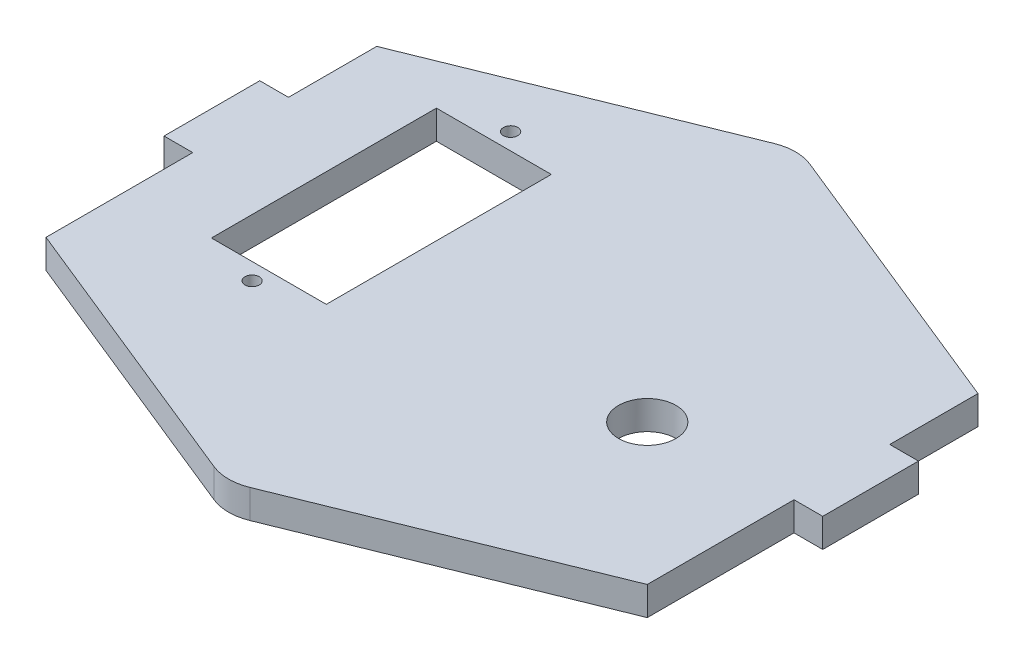
SolidWorks part; units mm, degrees
material "Acrylic (Medium-high impact)"
ref_plane "Front Plane" through (0, 0, 0) normal (0, 0, 1) x (1, 0, 0)
ref_plane "Top Plane" through (0, 0, 0) normal (0, 1, 0) x (1, 0, 0)
ref_plane "Right Plane" through (0, 0, 0) normal (1, 0, 0) x (0, 0, -1)
sketch "Sketch6" plane through (0, 0, 0) normal (0, 1, 0) x (1, 0, 0)
  line L0 (-34.4, 16.055) -> (0, 30)
  line L1 (0, -30) -> (34.4, -16.055)
  line L2 (34.4, -16.055) -> (34.4, 16.055)
  line L3 (-34.4, 0) -> (34.4, 0) construction
  line L4 (-34.4, -16.055) -> (-34.4, 16.055)
  line L5 (34.4, -16.055) -> (-34.4, 16.055) construction
  line L6 (34.4, 16.055) -> (-34.4, -16.055) construction
  line L7 (0, 30) -> (34.4, 16.055)
  line L8 (-34.4, -16.055) -> (0, -30)
  point P0 (0, 0)
  dimension "D1" = 68.8
  dimension "D2" = 32.11
  dimension "D3" = 30
  dimension "D4" = 37.119
  dimension "D5" = 37.119
extrude "Boss-Extrude4" add sketch "Sketch6" along normal blind 3
sketch "Sketch8" plane through (0, 3, 0) normal (0, 1, 0) x (1, 0, 0)
  line L0 (0, -30) -> (0, 30) construction
  line L1 (34.4, 16.055) -> (31.4, 16.055)
  line L2 (34.4, 16.055) -> (34.4, 8.055)
  line L3 (34.4, 8.055) -> (31.4, 8.055)
  line L4 (31.4, 16.055) -> (31.4, 8.055)
  line L5 (34.4, -16.055) -> (31.4, -16.055)
  line L6 (34.4, -16.055) -> (34.4, -1.945)
  line L7 (34.4, -1.945) -> (31.4, -1.945)
  line L8 (31.4, -16.055) -> (31.4, -1.945)
  line L9 (-34.4, -16.055) -> (-31.4, -16.055)
  line L10 (-31.4, -16.055) -> (-31.4, -1.945)
  line L11 (-34.4, -16.055) -> (-34.4, -1.945)
  line L12 (-34.4, -1.945) -> (-31.4, -1.945)
  line L13 (-34.4, 8.055) -> (-31.4, 8.055)
  line L14 (-34.4, 16.055) -> (-34.4, 8.055)
  line L15 (-31.4, 16.055) -> (-31.4, 8.055)
  line L16 (-34.4, 16.055) -> (-31.4, 16.055)
  dimension "D1" = 8
  dimension "D2" = 3
  dimension "D3" = 10
  dimension "D4" = 3
extrude "Cut-Extrude5" cut sketch "Sketch8" against normal blind 3
sketch "Sketch9" plane through (0, 3, 0) normal (0, 1, 0) x (1, 0, 0)
  line L0 (-34.4, 3.055) -> (34.4, 3.055) construction
  line L1 (-34.4, 8.055) -> (-34.4, -1.945) construction
  line L2 (34.4, -1.945) -> (34.4, 8.055) construction
  line L3 (0, 30) -> (0, -30) construction
  line L4 (-10.7, -8.695) -> (-22.7, -8.695)
  line L5 (-10.7, -8.695) -> (-10.7, 14.805)
  line L6 (-10.7, 14.805) -> (-22.7, 14.805)
  line L7 (-22.7, -8.695) -> (-22.7, 14.805)
  line L8 (-10.7, -8.695) -> (-22.7, 14.805) construction
  line L9 (-10.7, 14.805) -> (-22.7, -8.695) construction
  line L10 (34.4, 16.055) -> (0, 30) construction
  circle A0 centre (-16.7, 16.555) radius 0.75
  circle A1 centre (-16.7, -10.445) radius 0.75
  point P6 (-16.7, 3.055)
  dimension "D4" = 1.5
  dimension "D1" = 23.5
  dimension "D2" = 12
  dimension "D3" = 16.7
  dimension "D5" = 1.75
  dimension "D6" = 16.7
extrude "Cut-Extrude6" cut sketch "Sketch9" against normal blind 3
fillet "Fillet2" radius 5 2 edges at (0, 1.5, 30) (0, 1.5, -30)
sketch "Sketch10" plane through (0, 3, 0) normal (0, 1, 0) x (1, 0, 0)
  line L0 (31.4, 16.055) -> (31.4, 17.2711)
  line L1 (34.4, 16.055) -> (1.8784, 29.2385) construction
  line L2 (31.4, 17.2711) -> (34.4, 16.055)
  line L3 (34.4, 16.055) -> (31.4, 16.055)
  line L4 (-34.4, 3.055) -> (34.4, 3.055) construction
  line L5 (31.4, -16.055) -> (34.4, -16.055)
  line L6 (31.4, -16.055) -> (34.4, -16.055) construction
  line L7 (0, 29.6048) -> (0, -29.6048) construction
  line L8 (-34.4, 8.055) -> (-34.4, -1.945) construction
  line L9 (34.4, -1.945) -> (34.4, 8.055) construction
  line L10 (34.4, -16.055) -> (31.4, -17.2711)
  line L11 (1.8784, -29.2385) -> (34.4, -16.055) construction
  line L12 (31.4, -17.2711) -> (31.4, -16.055)
  line L13 (-31.4, -16.055) -> (-34.4, -16.055)
  line L14 (-34.4, -16.055) -> (-31.4, -17.2711)
  line L15 (-34.4, -16.055) -> (-1.8784, -29.2385) construction
  line L16 (-31.4, -17.2711) -> (-31.4, -16.055)
  line L17 (-31.4, 16.055) -> (-31.4, 17.2711)
  line L18 (-1.8784, 29.2385) -> (-34.4, 16.055) construction
  line L19 (-31.4, 17.2711) -> (-34.4, 16.055)
  line L20 (-31.4, 16.055) -> (-34.4, 16.055) construction
  line L21 (-34.4, 16.055) -> (-31.4, 16.055)
  arc A0 (1.8784, 29.2385) -> (-1.8784, 29.2385) centre (0, 24.6048) ccw construction
  arc A1 (-1.8784, -29.2385) -> (1.8784, -29.2385) centre (0, -24.6048) ccw construction
split "Split1" trim tools "Sketch10" bodies to split 110 resulting bodies 111 112 113 114 115
delete or keep bodies "Body-Delete1" type delete bodies bodies 111
delete or keep bodies "Body-Delete2" type delete bodies bodies 112
delete or keep bodies "Body-Delete3" type delete bodies bodies 113
delete or keep bodies "Body-Delete4" type delete bodies bodies 114
sketch "Sketch11" plane through (0, 3, 0) normal (0, 1, 0) x (1, 0, 0)
  line L0 (0, 29.6048) -> (0, -19.1211) construction
  arc A0 (1.8784, 29.2385) -> (-1.8784, 29.2385) centre (0, 24.6048) ccw construction
  circle A1 centre (16.7, -2.5711) radius 3
  dimension "D1" = 6
  dimension "D2" = 16.7
  dimension "D3" = 14.7
extrude "Cut-Extrude7" cut sketch "Sketch11" against normal blind 10
